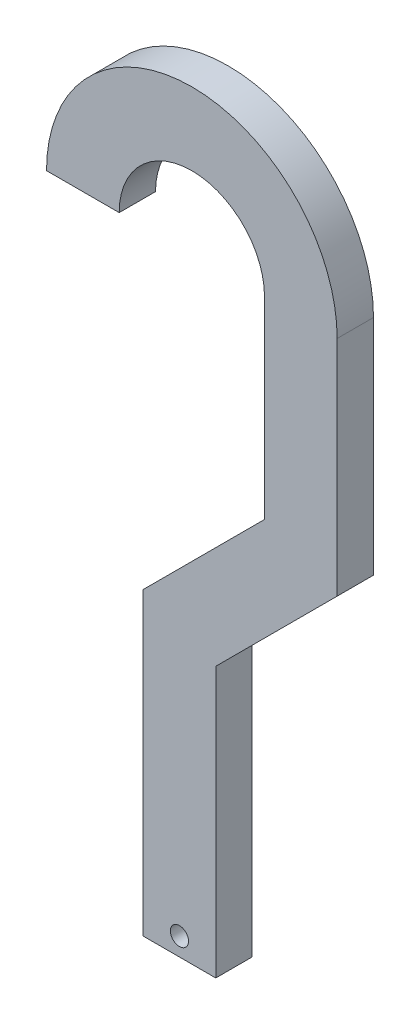
SolidWorks part; units mm, degrees
ref_plane "Front Plane" through (0, 0, 0) normal (0, 0, 1) x (1, 0, 0)
ref_plane "Top Plane" through (0, 0, 0) normal (0, 1, 0) x (1, 0, 0)
ref_plane "Right Plane" through (0, 0, 0) normal (1, 0, 0) x (0, 0, -1)
sketch "Sketch1" plane through (0, 0, 0) normal (0, 0, 1) x (1, 0, 0)
  line L1 (-25.4, 6.3913) -> (-25.4, 34.0623)
  line L2 (0, 0) -> (0, 34.0623)
  line L3 (-101.6, 34.0623) -> (-76.2, 34.0623)
  line L6 (-67.8354, -100.4036) -> (-67.8354, -180.7654)
  line L7 (-67.8354, -180.7654) -> (-42.4354, -180.7654)
  line L8 (-42.4354, -180.7654) -> (-42.4354, -86.3903)
  line L9 (-42.4354, -86.3903) -> (0, -43.9549)
  line L10 (0, -43.9549) -> (0, 0)
  line L11 (-25.4, 6.3913) -> (-25.4, -33.4339)
  line L12 (-25.4, -33.4339) -> (-67.8354, -75.8692)
  line L13 (-67.8354, -75.8692) -> (-67.8354, -100.4036)
  arc A0 (-25.4, 34.0623) -> (-76.2, 34.0623) centre (-50.8, 34.0623) ccw
  arc A1 (-101.6, 34.0623) -> (0, 34.0623) centre (-50.8, 34.0623) cw
  dimension "D1" = 25.4
  dimension "D5" = 25.4
  dimension "D2" = 25.4
  dimension "D3" = 135
  dimension "D4" = 25.4
extrude "Boss-Extrude1" add sketch "Sketch1" along normal blind 12.7 contours L8 L9 L10 L2 A1 L3 A0 L1 L11 L12 L13 L6 L7
sketch "Sketch2" plane through (0, 0, 12.7) normal (0, 0, 1) x (1, 0, 0)
  line L0 (-67.8354, -180.7654) -> (-42.4354, -180.7654) construction
  line L1 (-42.4354, -180.7654) -> (-42.4354, -86.3903) construction
  circle A0 centre (-55.1354, -174.4154) radius 3.175
  point P6 (-48.9382, -190.5015)
  dimension "D1" = 6.35
  dimension "D2" = 6.35
  dimension "D3" = 12.7
extrude "Cut-Extrude1" cut sketch "Sketch2" against normal up to surface (12.7 mm away) up to face at (-44.9142, -38.873, 0)
